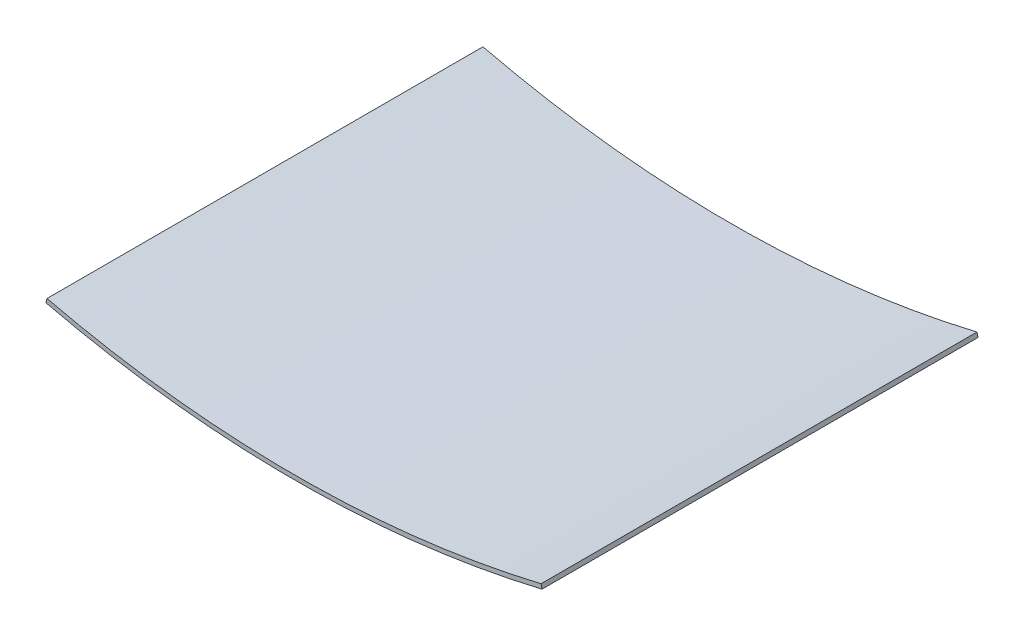
SolidWorks part; units mm, degrees
ref_plane "Alzado" through (0, 0, 0) normal (0, 0, 1) x (1, 0, 0)
ref_plane "Planta" through (0, 0, 0) normal (0, 1, 0) x (1, 0, 0)
ref_plane "Vista lateral" through (0, 0, 0) normal (1, 0, 0) x (0, 0, -1)
sketch "Croquis1" plane through (0, 0, 0) normal (0, 0, 1) x (1, 0, 0)
  line L0 (0, 0) -> (0, 25.4) construction
  line L1 (-215.9, 25.4) -> (215.9, 25.4) construction
  arc A0 (-215.9, 25.4) -> (215.9, 25.4) centre (0, 930.275) ccw
  dimension "D1" = 431.8
  dimension "D2" = 25.4
extrude "Extruir-Lámina1" add sketch "Croquis1" along normal blind 381 thin
